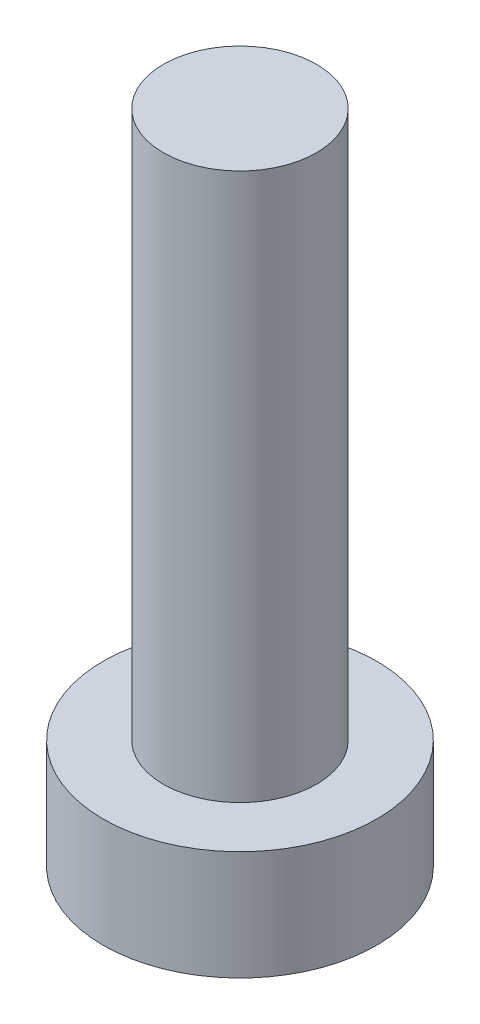
SolidWorks part; units mm, degrees
ref_plane "Front Plane" through (0, 0, 0) normal (0, 0, 1) x (1, 0, 0)
ref_plane "Top Plane" through (0, 0, 0) normal (0, 1, 0) x (1, 0, 0)
ref_plane "Right Plane" through (0, 0, 0) normal (1, 0, 0) x (0, 0, -1)
sketch "Sketch1" plane through (0, 0, 0) normal (1, 0, 0) x (0, 0, -1)
  line L0 (0, 94.8387) -> (0, -82.1935) construction
  line L1 (0, 58.7097) -> (7, 58.7097)
  line L2 (7, 58.7097) -> (7, 8.7097)
  line L3 (7, 8.7097) -> (12.5, 8.7097)
  line L4 (12.5, 8.7097) -> (12.5, -1.2903)
  line L5 (12.5, -1.2903) -> (0, -1.2903)
  line L6 (0, 58.7097) -> (0, -1.2903)
  dimension "D1" = 7
  dimension "D2" = 12.5
  dimension "D3" = 10
  dimension "D4" = 50
revolve "Revolve1" add sketch "Sketch1" angle 360 about L0
